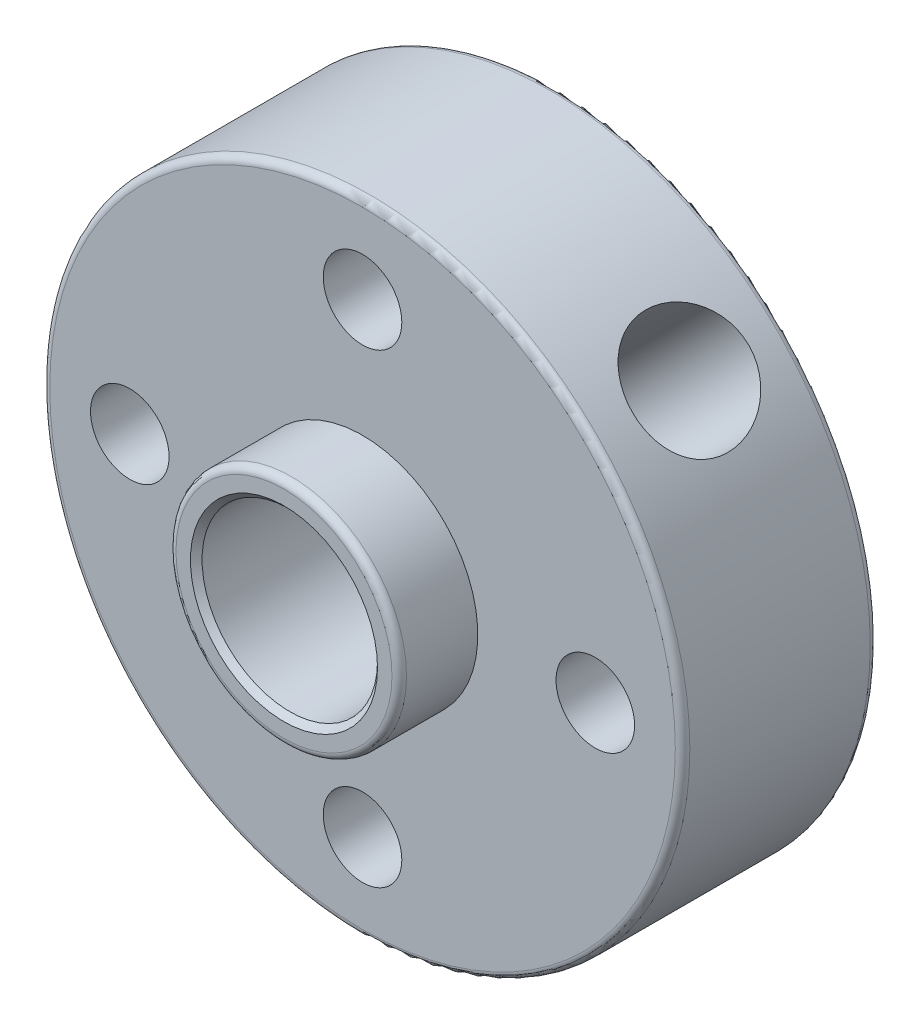
SolidWorks part; units mm, degrees
ref_plane "Front Plane" through (0, 0, 0) normal (0, 0, 1) x (1, 0, 0)
ref_plane "Top Plane" through (0, 0, 0) normal (0, 1, 0) x (1, 0, 0)
ref_plane "Right Plane" through (0, 0, 0) normal (1, 0, 0) x (0, 0, -1)
sketch "Sketch1" plane through (0, 0, 0) normal (0, 0, 1) x (1, 0, 0)
  circle A0 centre (0, 0) radius 11
  dimension "D1" = 22
extrude "Boss-Extrude1" add sketch "Sketch1" against normal blind 6.7
sketch "Sketch2" plane through (0, 0, 0) normal (0, 0, 1) x (1, 0, 0)
  circle A0 centre (0, 0) radius 3.9625
  dimension "D1" = 7.925
extrude "Boss-Extrude2" add sketch "Sketch2" along normal blind 2.7
sketch "Sketch3" plane through (0, 0, 2.7) normal (0, 0, 1) x (1, 0, 0)
  circle A0 centre (0, 0) radius 3.015
  dimension "D1" = 6.03
extrude "Cut-Extrude1" cut sketch "Sketch3" against normal through all
sketch "Sketch4" plane through (0, 0, 0) normal (0, 0, 1) x (1, 0, 0)
  circle A0 centre (0, 0) radius 8 construction
  circle A1 centre (0, 8) radius 1.35
  circle A2 centre (8, 0) radius 1.35
  circle A3 centre (0, -8) radius 1.35
  circle A4 centre (-8, 0) radius 1.35
  dimension "D1" = 16
  dimension "D2" = 2.7
  dimension "D3" = 2.7
  dimension "D4" = 2.7
  dimension "D5" = 2.7
extrude "Cut-Extrude2" cut sketch "Sketch4" against normal through all
cosmetic thread "Cosmetic Thread1" parameters "D2"=3.5052
cosmetic thread "Cosmetic Thread2" parameters "D2"=3.5052
cosmetic thread "Cosmetic Thread3" parameters "D2"=3.5052
cosmetic thread "Cosmetic Thread4" parameters "D2"=3.5052
sketch "Sketch5" plane through (0, 0, 0) normal (0, 0, 1) x (1, 0, 0)
  line L0 (0, 0) -> (10.8252, -10.8252) construction
ref_plane "Plane1" through (0, 0, 0) normal (-0.7071, -0.7071, 0) x (0, 0, 1)
sketch "Sketch6" plane through (0, 0, 0) normal (-0.7071, -0.7071, 0) x (0, 0, 1)
  line L0 (-6.7, 11) -> (-6.7, -11) construction
  circle A0 centre (-3.5, 0) radius 2
  dimension "D2" = 4
  dimension "D1" = 3.2
extrude "Cut-Extrude3" cut sketch "Sketch6" against normal through all
cosmetic thread "Cosmetic Thread5" parameters "D2"=4.826
chamfer "Chamfer1" distance 0.2 angle 45 2 edges at (3.015, 0, -6.7) (3.015, 0, 2.7)
fillet "Fillet1" radius 0.25 3 edges at (11, 0, -6.7) (11, 0, 0) (3.9625, 0, 2.7)
